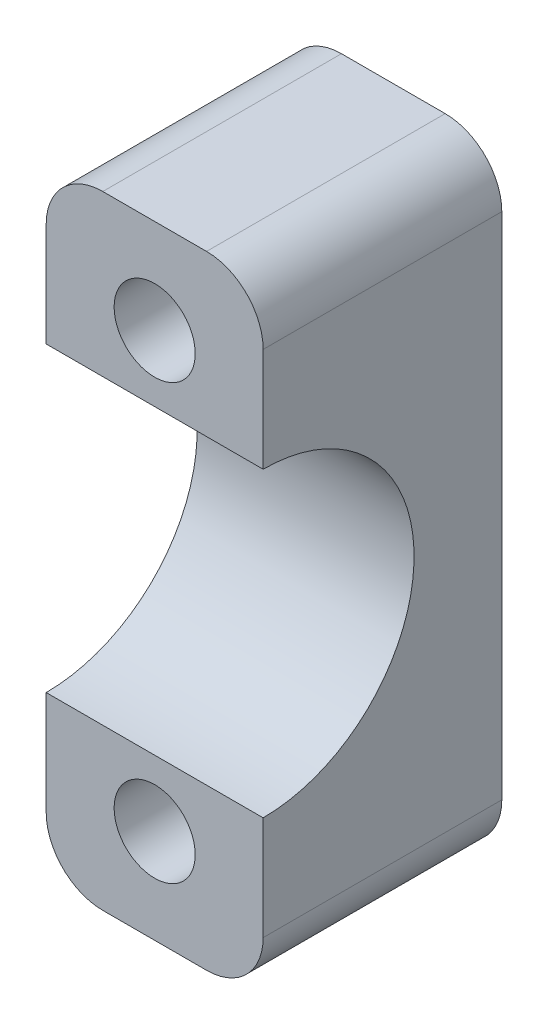
SolidWorks part; units mm, degrees
material "ABS"
ref_plane "Front Plane" through (0, 0, 0) normal (0, 0, 1) x (1, 0, 0)
ref_plane "Top Plane" through (0, 0, 0) normal (0, 1, 0) x (1, 0, 0)
ref_plane "Right Plane" through (0, 0, 0) normal (1, 0, 0) x (0, 0, -1)
sketch "Sketch1" plane through (0, 0, 0) normal (0, 0, 1) x (1, 0, 0)
  line L1 (-5.75, 16.5) -> (5.75, 16.5)
  line L2 (-5.75, 16.5) -> (-5.75, -16.5)
  line L3 (-5.75, -16.5) -> (5.75, -16.5)
  line L4 (5.75, 16.5) -> (5.75, -16.5)
  line L5 (-5.75, 16.5) -> (5.75, -16.5) construction
  line L6 (-5.75, -16.5) -> (5.75, 16.5) construction
  point P0 (0, 0)
  dimension "D1" = 33
  dimension "D2" = 11.5
extrude "Boss-Extrude1" add sketch "Sketch1" along normal blind 12.65
fillet "Fillet1" radius 3 4 edges at (5.75, -16.5, 6.325) (-5.75, -16.5, 6.325) (-5.75, 16.5, 6.325) (5.75, 16.5, 6.325)
sketch "Sketch2" plane through (5.75, 0, 0) normal (1, 0, 0) x (0, 0, -1)
  line L0 (-12.65, -13.5) -> (-12.65, 13.5) construction
  line L1 (-12.65, 8) -> (-12.65, -8)
  arc A0 (-12.65, -8) -> (-12.65, 8) centre (-12.65, 0) ccw
  dimension "D1" = 16
extrude "Cut-Extrude1" cut sketch "Sketch2" against normal up to next
hole_wizard "CBORE for M4 SHCS1" positions "Sketch4" profile "Sketch5" counterbore size "M4" standard "ANSI Metric" end condition through all
sketch "Sketch4" plane through (0, 0, 0) normal (0, 0, -1) x (-1, 0, 0)
  line L0 (0, 11.5) -> (0, -11.5) construction
  point P0 (0, 11.5)
  point P2 (0, -11.5)
  dimension "D1" = 23
sketch "Sketch5" plane through (0, 11.5, 0) normal (1, 0, 0) x (0, 1, 0)
  line L0 (0, 0) -> (0, 12.65)
  line L1 (0, 12.65) -> (2.15, 12.65)
  line L3 (2.15, 12.65) -> (2.15, 4)
  line L4 (2.15, 4) -> (4, 4)
  line L5 (4, 4) -> (4, 0)
  line L7 (4, 0) -> (0, 0)
  line L11 (0, -6.35) -> (0, 107.95) construction
  dimension "Thru Hole Dia." = 4.3
  dimension "Thru Hole Depth" = 12.65
  dimension "C'Bore Dia." = 8
  dimension "C'Bore Depth" = 4
